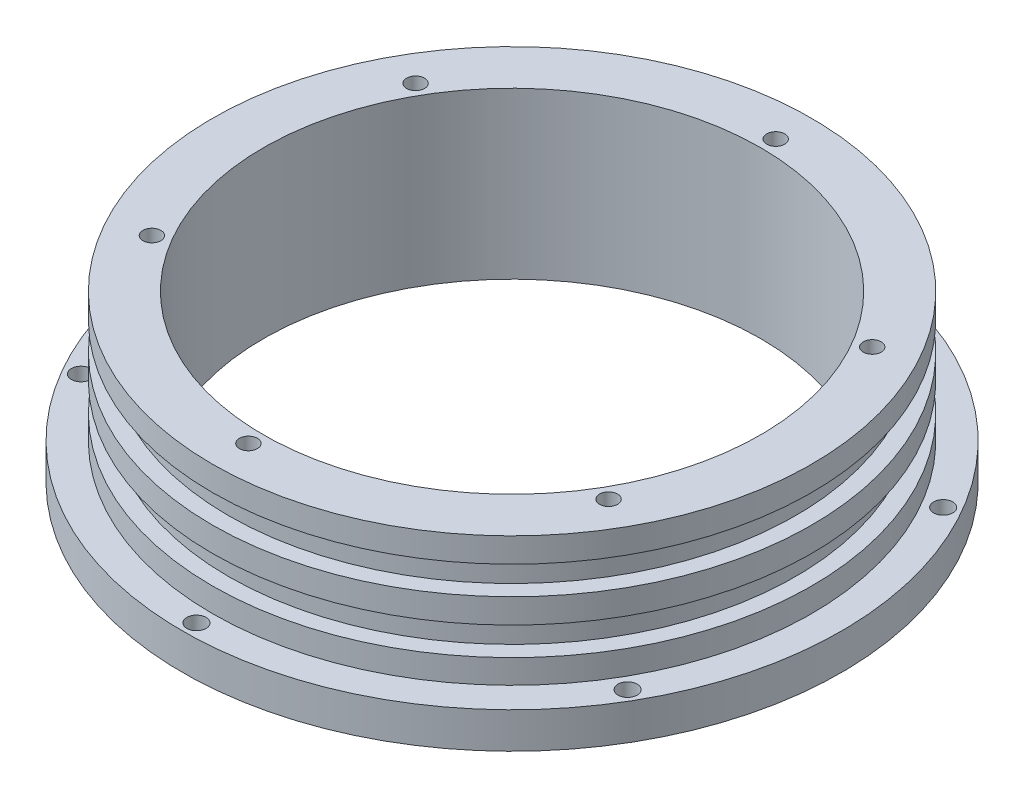
SolidWorks part; units mm, degrees
material "6061 合金"
ref_plane "前视基准面" through (0, 0, 0) normal (0, 0, 1) x (1, 0, 0)
ref_plane "上视基准面" through (0, 0, 0) normal (0, 1, 0) x (1, 0, 0)
ref_plane "右视基准面" through (0, 0, 0) normal (1, 0, 0) x (0, 0, -1)
sketch "草图1" plane through (0, 0, 0) normal (0, 1, 0) x (1, 0, 0)
  circle A0 centre (0, 0) radius 55
  circle A1 centre (0, 0) radius 41.5
  dimension "D1" = 110
  dimension "D2" = 83
extrude "凸台-拉伸1" add sketch "草图1" along normal blind 27.6
sketch "草图2" plane through (0, 27.6, 0) normal (0, 1, 0) x (1, 0, 0)
  circle A0 centre (0, 0) radius 50
  circle A1 centre (0, 0) radius 55
  dimension "D1" = 100
  dimension "D2" = 110
extrude "切除-拉伸1" cut sketch "草图2" against normal blind 21.6
sketch "草图3" plane through (0, 0, 0) normal (0, 0, 1) x (1, 0, 0)
  line L0 (-50, 27.6) -> (-50, 6) construction
  line L1 (-50, 23.5) -> (-47.3, 23.5)
  line L2 (-50, 23.5) -> (-50, 18.8)
  line L3 (-50, 18.8) -> (-47.3, 18.8)
  line L4 (-47.3, 23.5) -> (-47.3, 18.8)
  line L5 (50, 27.6) -> (-50, 27.6) construction
  line L6 (-50, 14.7) -> (-50, 10)
  line L7 (-50, 14.7) -> (-47.3, 14.7)
  line L8 (-47.3, 14.7) -> (-47.3, 10)
  line L9 (-50, 10) -> (-47.3, 10)
  line L10 (0, 0) -> (0, 57.28) construction
  line L11 (-55, 0) -> (55, 0) construction
  dimension "D1" = 2.7
  dimension "D2" = 4.7
  dimension "D3" = 8.8
  dimension "D5" = 4.1
  dimension "D4" = 2
revolve "切除-旋转1" cut sketch "草图3" angle 360 about L10
sketch "草图4" plane through (0, 0, 0) normal (0, -1, 0) x (1, 0, 0)
  circle A0 centre (0, 0) radius 46
  circle A1 centre (0, 0) radius 50
  dimension "D1" = 92
  dimension "D2" = 100
extrude "切除-拉伸2" cut sketch "草图4" against normal blind 2.7
sketch "草图5" plane through (0, 0, 0) normal (0, -1, 0) x (1, 0, 0)
  line L0 (0, 0) -> (136.1507, 0) construction
  line L1 (0, 0) -> (0, 67.4698) construction
  line L2 (0, 0) -> (105.1724, 60.7213) construction
  circle A0 centre (45.6127, 26.3345) radius 1.6
  circle A1 centre (45.6127, -26.3345) radius 1.6
  circle A2 centre (0, -52.6691) radius 1.6
  circle A3 centre (-45.6127, -26.3345) radius 1.6
  circle A4 centre (-45.6127, 26.3345) radius 1.6
  circle A5 centre (0, 52.6691) radius 1.6
  point P20 (0, 0)
  dimension "D2" = 3.2
  dimension "D3" = 52.6691
  dimension "D1" = 30
  dimension "D4" = 6
extrude "切除-拉伸3" cut sketch "草图5" against normal through all
sketch "草图6" plane through (0, 27.6, 0) normal (0, 1, 0) x (1, 0, 0)
  line L0 (0, 0) -> (98.0631, 0) construction
  line L1 (0, 0) -> (94.0512, 54.3005) construction
  circle A0 centre (38.1051, 22) radius 1.5
  circle A1 centre (38.1051, -22) radius 1.5
  circle A2 centre (0, -44) radius 1.5
  circle A3 centre (-38.1051, -22) radius 1.5
  circle A4 centre (-38.1051, 22) radius 1.5
  circle A5 centre (0, 44) radius 1.5
  point P18 (0, 0)
  dimension "D2" = 3
  dimension "D3" = 44
  dimension "D1" = 30
  dimension "D4" = 6
extrude "切除-拉伸4" cut sketch "草图6" against normal blind 6
